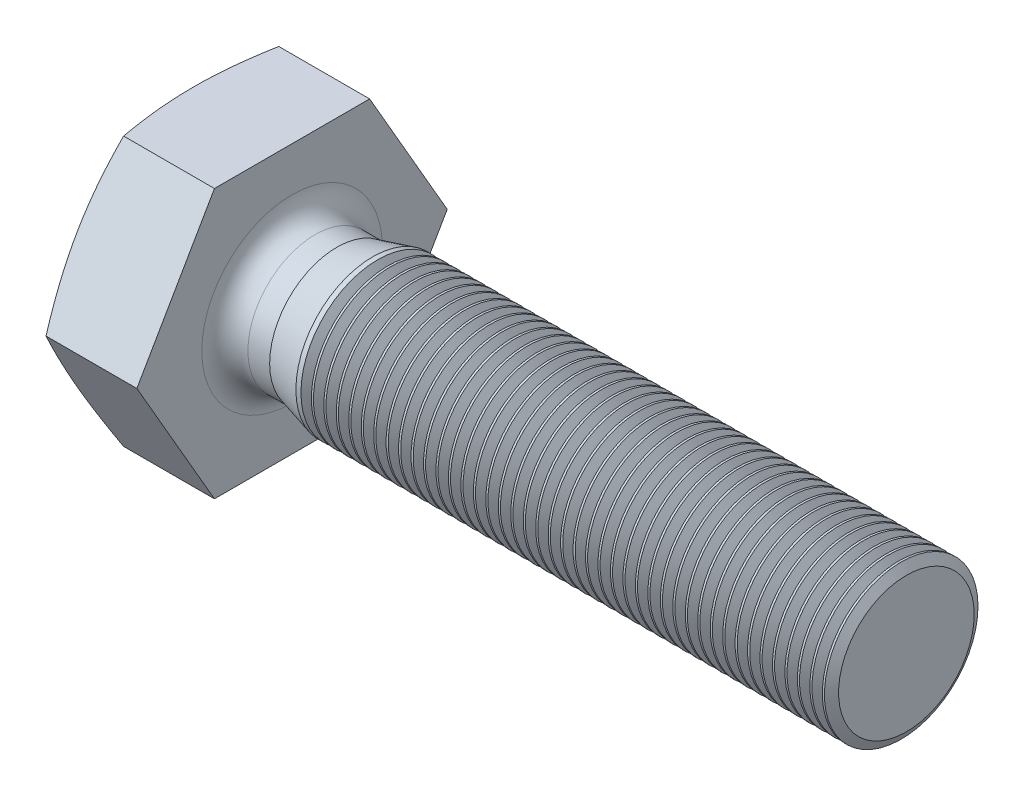
SolidWorks part; units mm, degrees
ref_plane "Front" through (0, 0, 0) normal (0, 0, 1) x (1, 0, 0)
ref_plane "Top" through (0, 0, 0) normal (0, 1, 0) x (1, 0, 0)
ref_plane "Right" through (0, 0, 0) normal (1, 0, 0) x (0, 0, -1)
other "Configuration Table"
sketch "Sketch2" plane through (0, 0, 0) normal (1, 0, 0) x (0, 0, -1)
  line L1 (2.0207, -3.5) -> (4.0415, 0)
  line L2 (4.0415, 0) -> (2.0207, 3.5)
  line L3 (2.0207, 3.5) -> (-2.0207, 3.5)
  line L4 (-2.0207, 3.5) -> (-4.0415, 0)
  line L5 (-4.0415, 0) -> (-2.0207, -3.5)
  line L6 (-2.0207, -3.5) -> (2.0207, -3.5)
  circle A0 centre (0, 0) radius 3.5 construction
  dimension "s" = 7
extrude "BaseHead" add sketch "Sketch2" along normal blind 2.8
sketch "Sketch10" plane through (0, 0, 0) normal (0, 1, 0) x (1, 0, 0)
  line L0 (0, 0) -> (15.3195, 0) construction
  line L1 (2.8, 2.35) -> (2.8, 0)
  line L2 (2.8, 0) -> (18.8, 0)
  line L3 (2.8, 2.0207) -> (2.8, -2.0207) construction
  line L4 (4.9, 2) -> (18.8, 2)
  line L5 (18.8, 0) -> (18.8, 2)
  line L6 (3.4, 1.75) -> (3.967, 1.75)
  line L7 (2.8, 4.0415) -> (2.8, 2.0207) construction
  line L8 (4.9, 2) -> (3.967, 1.75)
  line L9 (2.8, 4.0415) -> (2.8, 2.0207) construction
  arc A0 (2.8, 2.35) -> (3.4, 1.75) centre (3.4, 2.35) ccw
  dimension "r" = 0.6
  dimension "d" = 4
  dimension "a" = 2.1
  dimension "Da" = 4.7
  dimension "D1" = 15
revolve "Revolve1" add sketch "Sketch10" angle 360 about L0
cosmetic thread "ThreadCosmetic1" [suppressed] parameters "D2"=3.459
sketch "Sketch5" plane through (0, 0, 0) normal (0, 1, 0) x (1, 0, 0)
  line L0 (0, 4.0415) -> (0.4337, 4.0415)
  line L1 (0, 4.0415) -> (0, 2.0207) construction
  line L2 (0.4337, 4.0415) -> (0, 2.85)
  line L3 (2.8, 4.0415) -> (0, 4.0415) construction
  line L4 (0, 2.85) -> (0, 4.0415)
  line L5 (-0.3584, 0) -> (3.3946, 0) construction
  dimension "dw" = 5.7
  dimension "D2" = 20
revolve "HeadChamfer" cut sketch "Sketch5" angle 360 about L5
ref_plane "Plane1" through (1, 0, 0) normal (1, 0, 0) x (0, 0, -1)
sketch "Sketch6" plane through (0, 0, 0) normal (-1, 0, 0) x (0, 0, 1)
  circle A0 centre (0, 0) radius 2.85
  dimension "D1" = 5.7
extrude "Cut-Extrude1" cut sketch "Sketch6" against normal blind 1
sketch "Sketch7" plane through (0, 0, 0) normal (0, 1, 0) x (1, 0, 0)
  line L0 (1, 0) -> (6.7401, 0) construction
  line L1 (1, 2.85) -> (1, -2.85) construction
  line L2 (2.93, 0) -> (0.5, 2.5181)
  line L4 (0.5, 2.5181) -> (0.5, -2.5181)
  line L5 (0.5, -2.5181) -> (2.93, 0)
  line L7 (1, 2) -> (1, -2) construction
  dimension "m" = 4
  dimension "D1" = 0.5
  dimension "h" = 1.93
extrude "Cut-Extrude2" cut sketch "Sketch7" against normal mid plane 0.772
pattern_circular "CirPattern2" count 2 every 90 about axis through (0, 0, 0) along (1, 0, 0) of "Cut-Extrude2"
sketch "Sketch8" plane through (0, 0, 0) normal (0, 0, 1) x (1, 0, 0)
  line L0 (18.8, 1.7657) -> (18.9352, 2)
  line L1 (18.9352, 2) -> (18.9352, 2.2705)
  line L2 (18.9352, 2.2705) -> (18.6648, 2.2705)
  line L3 (18.6648, 2.2705) -> (18.6648, 2)
  line L4 (18.6648, 2) -> (18.8, 1.7657)
  line L5 (14.8, 0) -> (0, 0) construction
  line L6 (18.8, -2) -> (18.8, 2) construction
  line L7 (18.8, 2) -> (4.9, 2) construction
  dimension "D1" = 0.2705
revolve "Cut-Revolve10" cut sketch "Sketch8" angle 360 about L5
pattern_linear "LPattern10" count 43 spacing 0.3246 along (-1, 0, 0) of "Cut-Revolve10"
equation "\"D1@Sketch6\" = \"dw@Sketch5\""
equation "\"D1@Cut-Extrude1\" = \"k@BaseHead\" - \"k1@Plane1\""
equation "\"t@Cut-Extrude2\" = 0.4 * \"h@Sketch7\""
equation "\"D1@Sketch8\" =  ( \"d@Sketch10\" - \"D2@ThreadCosmetic1\" )  / 2"
equation "\"pitch@LPattern10\" = \"D1@Sketch8\" * 1.2"
equation "\"D1@LPattern10\" =  ( \"l@Sketch10\" - \"a@Sketch10\" )  / \"pitch@LPattern10\""
